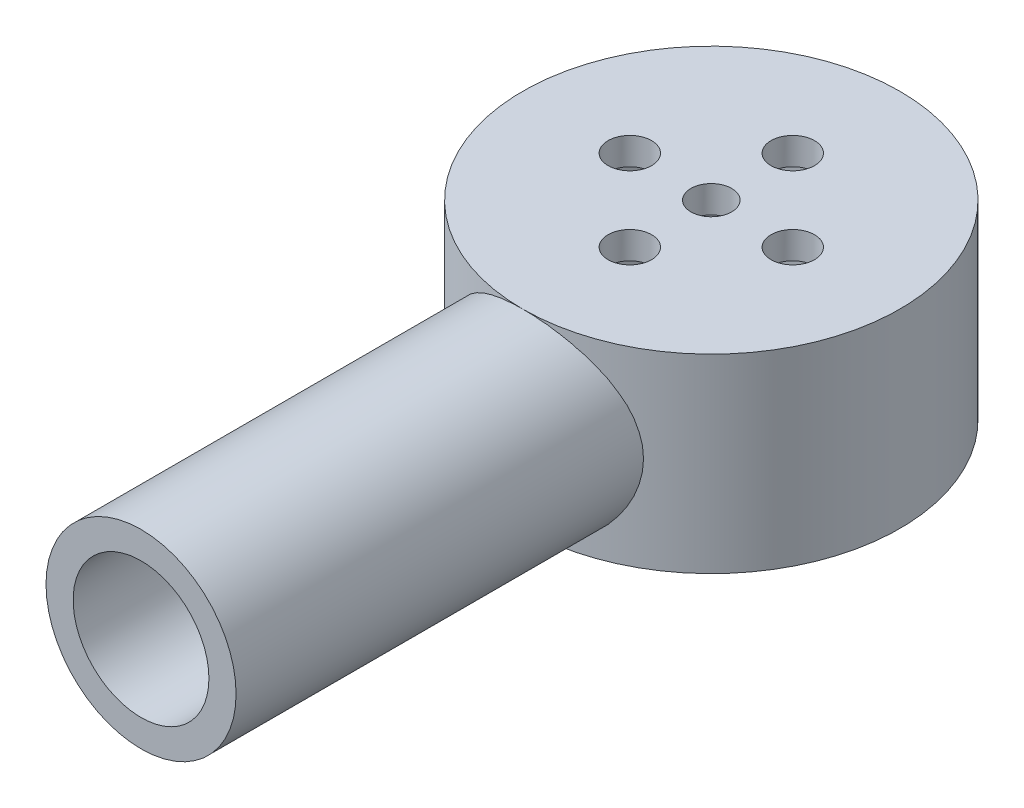
SolidWorks part; units mm, degrees
material "PLA"
ref_plane "Front Plane" through (0, 0, 0) normal (0, 0, 1) x (1, 0, 0)
ref_plane "Top Plane" through (0, 0, 0) normal (0, 1, 0) x (1, 0, 0)
ref_plane "Right Plane" through (0, 0, 0) normal (1, 0, 0) x (0, 0, -1)
sketch "Sketch1" plane through (0, 0, 0) normal (0, 0, 1) x (1, 0, 0)
  circle A0 centre (0, 0) radius 5
  circle A1 centre (0, 0) radius 7
  dimension "D1" = 10
  dimension "D2" = 2
extrude "Boss-Extrude1" add sketch "Sketch1" against normal blind 30 contours A1 A0
sketch "Sketch3" plane through (0, 0, 0) normal (0, 1, 0) x (1, 0, 0)
  line L0 (5, 30) -> (-5, 30) construction
  line L1 (0, 42) -> (0, 30) construction
  circle A0 centre (0, 42) radius 13.8924
  circle A1 centre (0, 42) radius 6 construction
  circle A2 centre (0, 48) radius 1.6
  circle A3 centre (6, 42) radius 1.6
  circle A4 centre (-6, 42) radius 1.6
  circle A5 centre (0, 36) radius 1.6
  circle A6 centre (0, 42) radius 1.5
  dimension "D2" = 12
  dimension "D3" = 3.2
  dimension "D4" = 3
  dimension "D1" = 12
extrude "Boss-Extrude2" add sketch "Sketch3" against normal blind 14 from offset 7 separate body contours A0 A6 A5 A4 A3 A2
sketch "Sketch4" plane through (0, -7, 0) normal (0, -1, 0) x (1, 0, 0)
  circle A0 centre (0, -42) radius 11.8924
  circle A1 centre (0, -42) radius 13.8924 construction
  dimension "D1" = 2
extrude "Cut-Extrude1" cut sketch "Sketch4" against normal blind 12
equation "\"DD_ShaftDiameterMm\"= 3"
equation "\"DD_BoltCircleMm\"= 12"
equation "\"DD_BoltHoleDiameterMm\"= 3.2"
equation "\"DD_MotorOuterDiameterMm\"= 24"
equation "\"DD_ArmTubeOdMm\"= 10"
equation "\"D1@Sketch1\"=\"DD_ArmTubeOdMm\""
equation "\"D1@Sketch3\"=\"DD_MotorOuterDiameterMm\"/2"
equation "\"D2@Sketch3\"=\"DD_BoltCircleMm\""
equation "\"D3@Sketch3\"=\"DD_BoltHoleDiameterMm\""
equation "\"D4@Sketch3\"=\"DD_ShaftDiameterMm\""
equation "\"D19@Boss-Extrude2\"=(\"DD_ArmTubeOdMm\"/2)+2"
equation "\"D1@Boss-Extrude2\"=\"DD_ArmTubeOdMm\"+4"
equation "\"D1@Cut-Extrude1\"=\"DD_ArmTubeOdMm\"+2"
